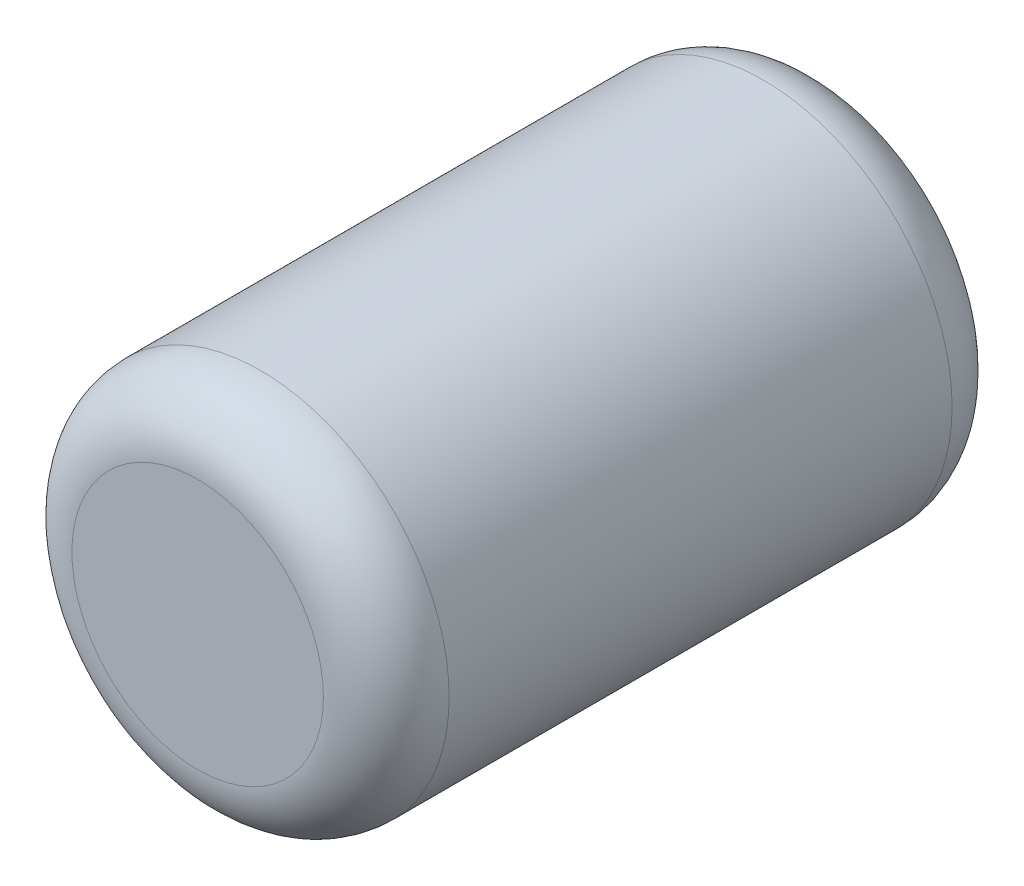
SolidWorks part; units mm, degrees
ref_plane "前视基准面" through (0, 0, 0) normal (0, 0, 1) x (1, 0, 0)
ref_plane "上视基准面" through (0, 0, 0) normal (0, 1, 0) x (1, 0, 0)
ref_plane "右视基准面" through (0, 0, 0) normal (1, 0, 0) x (0, 0, -1)
sketch "草图1" plane through (0, 0, 0) normal (0, 0, 1) x (1, 0, 0)
  circle A0 centre (0, 0) radius 1.5
  dimension "D1" = 3
extrude "凸台-拉伸1" add sketch "草图1" along normal blind 5
fillet "圆角1" radius 0.5 2 edges at (1.5, 0, 0) (1.5, 0, 5)
